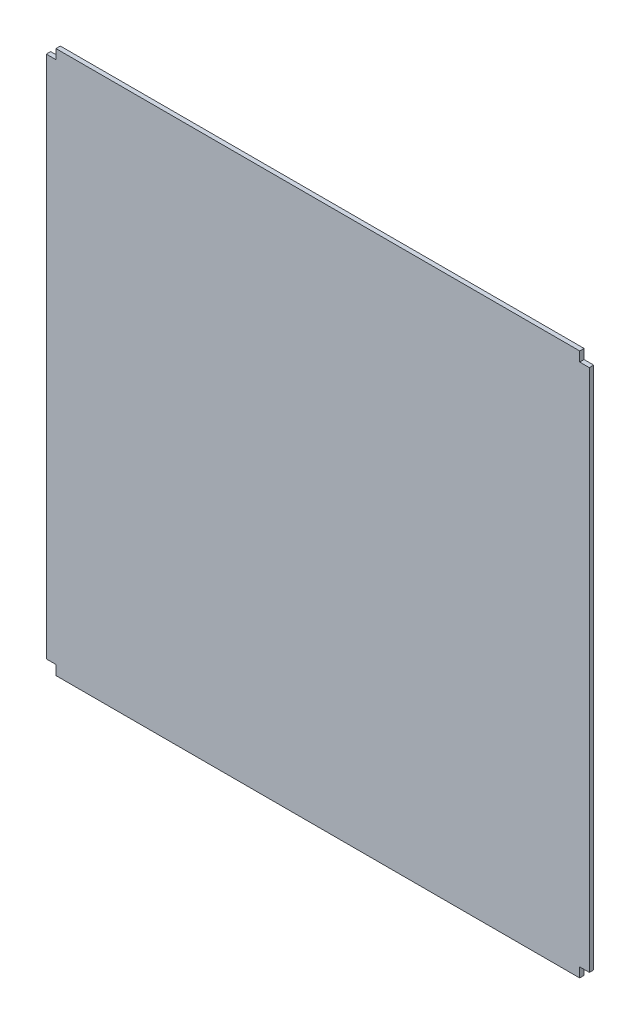
SolidWorks part; units mm, degrees
ref_plane "Plan de face" through (0, 0, 0) normal (0, 0, 1) x (1, 0, 0)
ref_plane "Plan de dessus" through (0, 0, 0) normal (0, 1, 0) x (1, 0, 0)
ref_plane "Plan de droite" through (0, 0, 0) normal (1, 0, 0) x (0, 0, -1)
sketch "Esquisse1" plane through (0, 0, 0) normal (0, 0, 1) x (1, 0, 0)
  line L0 (-299, 310) -> (-310, 310)
  line L1 (-310, -310) -> (310, -310)
  line L2 (-310, -310) -> (-310, 310)
  line L3 (-310, 310) -> (310, 310)
  line L4 (310, -310) -> (310, 310)
  line L5 (-310, -310) -> (310, 310) construction
  line L6 (-310, 310) -> (310, -310) construction
  line L7 (-299, 310) -> (-299, 299)
  line L8 (-310, 310) -> (-310, 299)
  line L9 (-299, 299) -> (-310, 299)
  line L10 (310, 310) -> (310, 299)
  line L11 (310, 310) -> (299, 310)
  line L12 (310, 299) -> (299, 299)
  line L13 (299, 310) -> (299, 299)
  line L14 (310, -310) -> (299, -310)
  line L15 (310, -310) -> (310, -299)
  line L16 (299, -310) -> (299, -299)
  line L17 (310, -299) -> (299, -299)
  line L18 (-299, -310) -> (-310, -310)
  line L19 (-299, -310) -> (-299, -299)
  line L20 (-310, -310) -> (-310, -299)
  line L21 (-299, -299) -> (-310, -299)
  point P0 (0, 0)
  dimension "D1" = 620
  dimension "D2" = 620
  dimension "D3" = 11
  dimension "D4" = 11
  dimension "D5" = 11
  dimension "D6" = 11
  dimension "D7" = 11
  dimension "D8" = 11
  dimension "D9" = 11
  dimension "D10" = 11
extrude "Boss.-Extru.1" add sketch "Esquisse1" along normal blind 5 contours L21 L19 L1 L16 L17 L4 L12 L13 L3 L7 L9 L2
